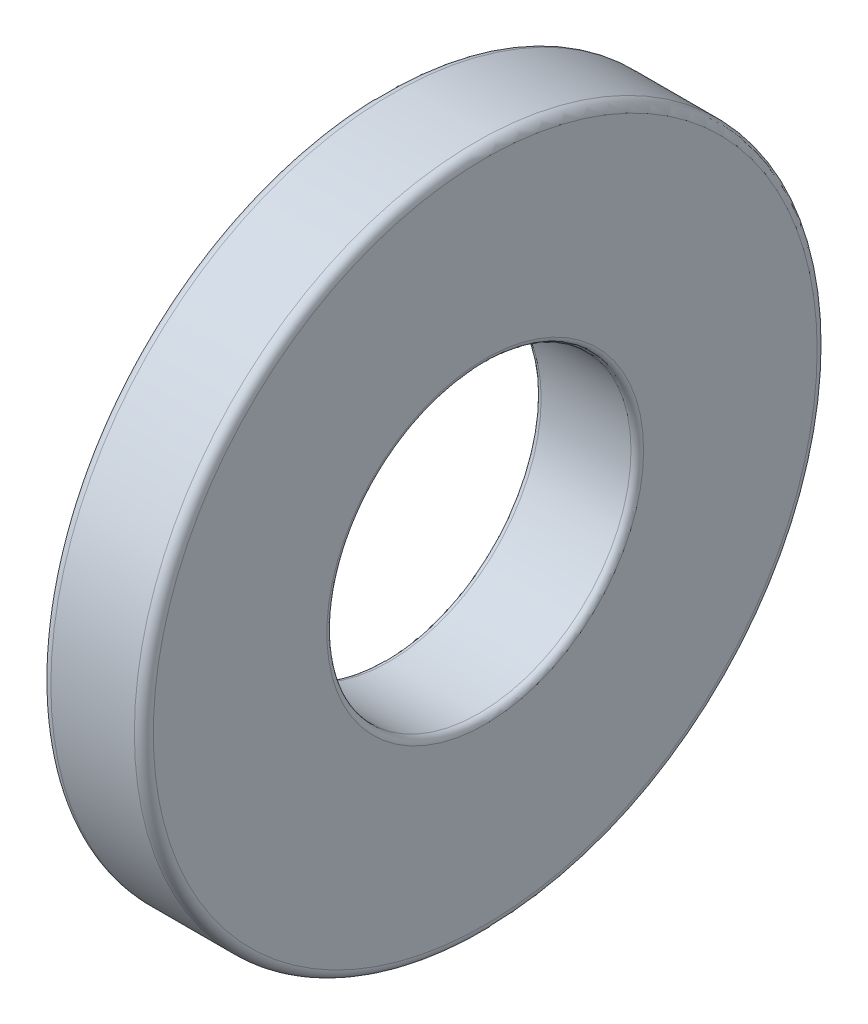
SolidWorks part; units mm, degrees
ref_plane "Front Plane" through (0, 0, 0) normal (0, 0, 1) x (1, 0, 0)
ref_plane "Top Plane" through (0, 0, 0) normal (0, 1, 0) x (1, 0, 0)
ref_plane "Right Plane" through (0, 0, 0) normal (1, 0, 0) x (0, 0, -1)
sketch "Sketch1" plane through (0, 0, 0) normal (1, 0, 0) x (0, 0, -1)
  circle A0 centre (0, 0) radius 5.5
  circle A1 centre (0, 0) radius 2.45
  dimension "D1" = 11
  dimension "D2" = 4.9
extrude "Boss-Extrude1" add sketch "Sketch1" along normal blind 1.65
fillet "Fillet1" radius 0.1524 2 edges at (0, 0, -5.5) (1.65, 0, -5.5)
fillet "Fillet2" radius 0.1016 2 edges at (0, 0, -2.45) (1.65, 0, -2.45)
